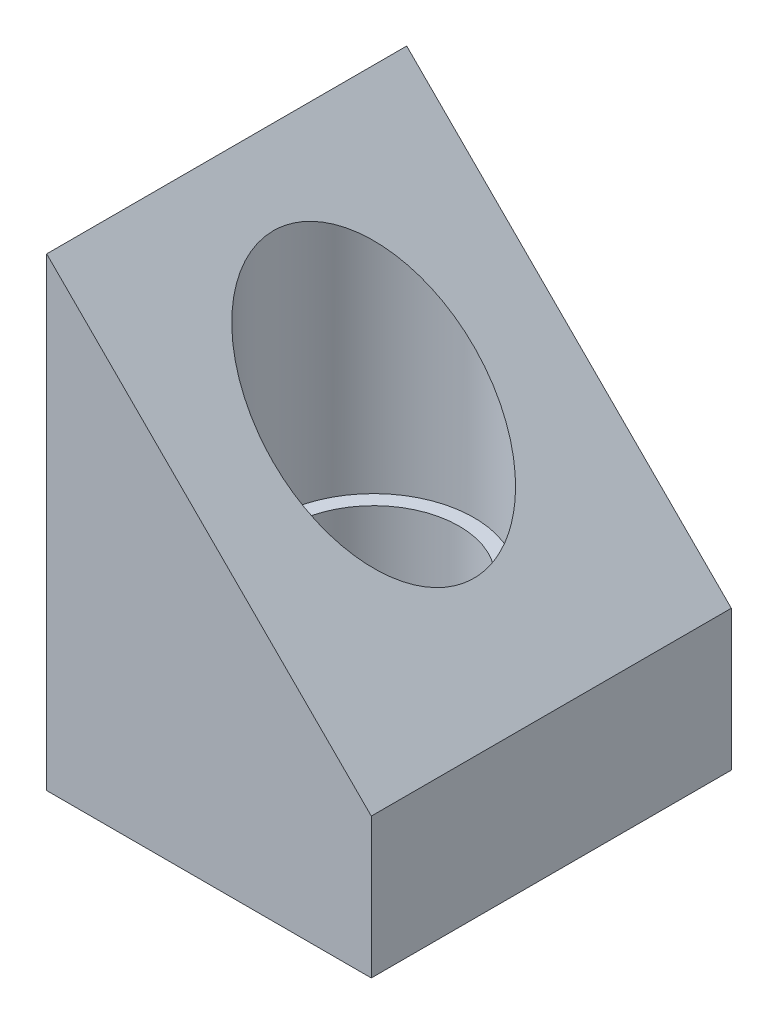
SolidWorks part; units mm, degrees
ref_plane "Front Plane" through (0, 0, 0) normal (0, 0, 1) x (1, 0, 0)
ref_plane "Top Plane" through (0, 0, 0) normal (0, 1, 0) x (1, 0, 0)
ref_plane "Right Plane" through (0, 0, 0) normal (1, 0, 0) x (0, 0, -1)
ref_plane "Plane1" through (0, -13.3, 0) normal (0, 1, 0) x (1, 0, 0)
sketch "Sketch1" plane through (0, -13.3, 0) normal (0, 1, 0) x (1, 0, 0)
  line L0 (18.5, -49.5) -> (12, -49.5) construction
  line L1 (18.25, -55.6) -> (12.75, -55.6)
  line L2 (18.25, -55.6) -> (18.25, -49.5)
  line L3 (18.25, -49.5) -> (12.75, -49.5)
  line L4 (12.75, -55.6) -> (12.75, -49.5)
  line L5 (18.25, -55.6) -> (12.75, -49.5) construction
  line L6 (18.25, -49.5) -> (12.75, -55.6) construction
  line L8 (21, -172.5) -> (21, 0) construction
  circle A0 centre (15.5, -52.55) radius 1.45 construction
  dimension "D1" = 2.9
  dimension "D2" = 2.75
  dimension "D3" = 5.5
extrude "Boss-Extrude1" add sketch "Sketch1" along normal blind 1
sketch "Sketch2" plane through (0, -12.3, 0) normal (0, 1, 0) x (1, 0, 0)
  line L4 (12.75, -49.5) -> (12.75, -55.6)
  line L5 (12.75, -55.6) -> (18.25, -55.6)
  line L6 (18.25, -55.6) -> (18.25, -49.5)
  line L7 (18.25, -49.5) -> (12.75, -49.5)
  line L8 (12.75, -49.5) -> (12.75, -55.6)
  line L9 (12.75, -55.6) -> (18.25, -55.6)
  line L10 (18.25, -55.6) -> (18.25, -49.5)
  line L11 (18.25, -49.5) -> (12.75, -49.5)
  circle A0 centre (15.24, -52.55) radius 1.45
  dimension "D2" = 2.9
  dimension "D1" = 0
extrude "Boss-Extrude2" add sketch "Sketch2" along normal offset from surface (1.3757 mm away) 0.3
ref_plane "Plane2" through (0, -5.4243, 0) normal (0, 1, 0) x (1, 0, 0)
sketch "Sketch3" plane through (0, -5.4243, 0) normal (0, 1, 0) x (1, 0, 0)
  circle A0 centre (15.24, -52.55) radius 1.7
  dimension "D1" = 3.4
extrude "Cut-Extrude1" cut sketch "Sketch3" against normal blind 5
